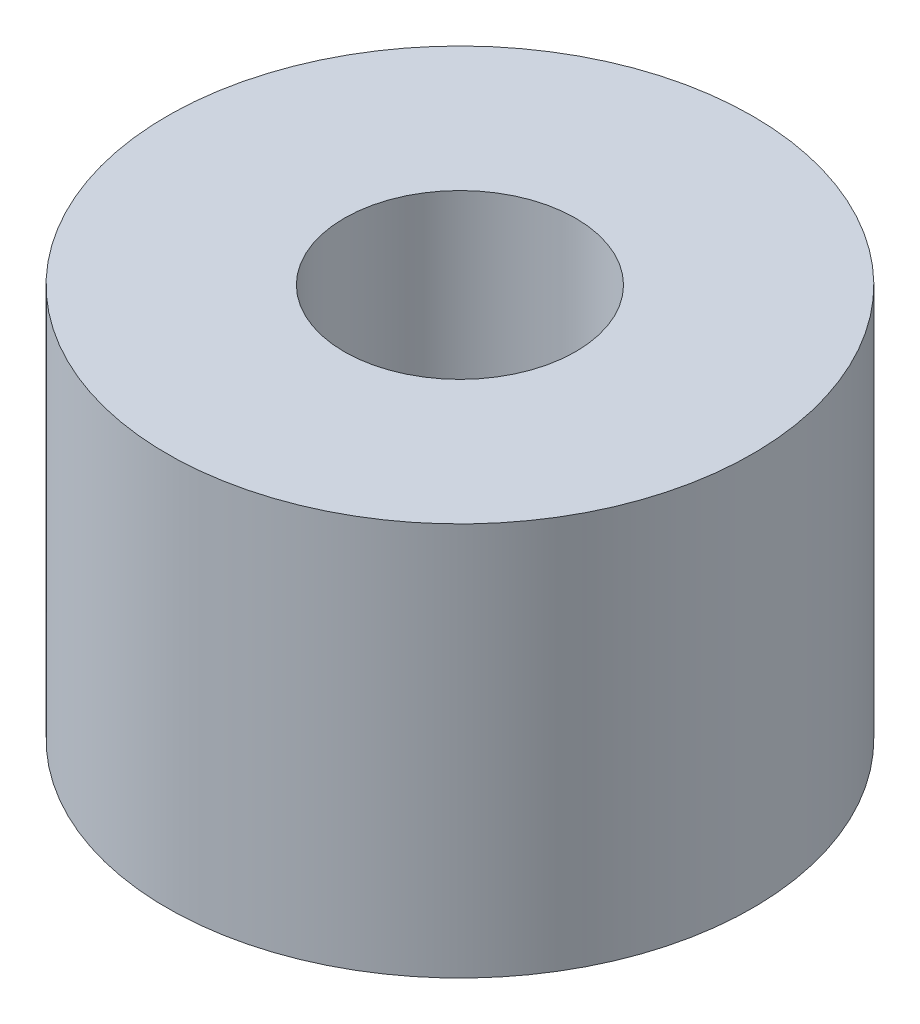
SolidWorks part; units mm, degrees
ref_plane "Piano frontale" through (0, 0, 0) normal (0, 0, 1) x (1, 0, 0)
ref_plane "Piano superiore" through (0, 0, 0) normal (0, 1, 0) x (1, 0, 0)
ref_plane "Piano destro" through (0, 0, 0) normal (1, 0, 0) x (0, 0, -1)
sketch "Schizzo1" plane through (0, 0, 0) normal (0, 0, 1) x (1, 0, 0)
  line L0 (0, 0) -> (0, 12.0036) construction
  line L1 (3.795, 0) -> (1.5, 0)
  line L2 (1.5, 0) -> (1.5, 5.1)
  line L3 (1.5, 5.1) -> (3.795, 5.1)
  line L4 (3.795, 5.1) -> (3.795, 0)
  dimension "D1" = 7.59
  dimension "D2" = 5.1
  dimension "D3" = 3
revolve "Rivoluzione1" add sketch "Schizzo1" angle 360 about L0
